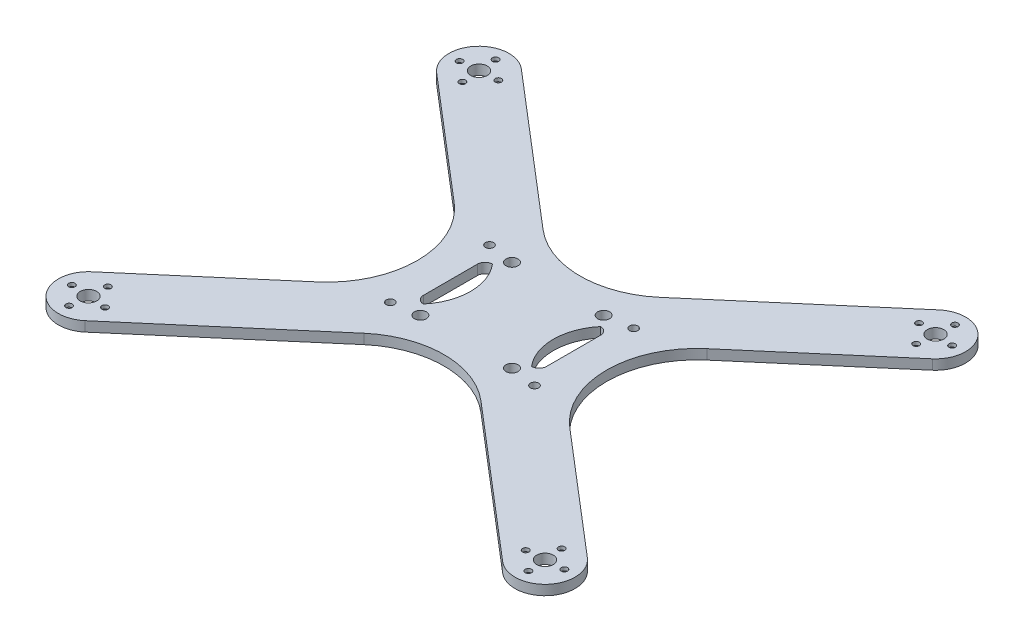
SolidWorks part; units mm, degrees
ref_plane "Front Plane" through (0, 0, 0) normal (0, 0, 1) x (1, 0, 0)
ref_plane "Top Plane" through (0, 0, 0) normal (0, 1, 0) x (1, 0, 0)
ref_plane "Right Plane" through (0, 0, 0) normal (1, 0, 0) x (0, 0, -1)
sketch "Sketch1" plane through (0, 0, 0) normal (0, 1, 0) x (1, 0, 0)
  line L0 (-75.9934, 65) -> (75.9934, -65) construction
  line L5 (-38.759, -33.152) -> (23.5603, 20.152) construction
  line L6 (-38.759, 33.152) -> (23.5603, -20.152) construction
  line L7 (75.9934, 65) -> (-75.9934, -65) construction
  line L8 (-82.4934, 57.4007) -> (-42.0385, 22.798)
  line L9 (82.4934, -57.4007) -> (42.0385, -22.798)
  line L10 (69.4934, 72.5993) -> (19.5, 29.8381)
  line L11 (-69.4934, -72.5993) -> (-19.5, -29.8381)
  line L12 (19.5, -29.8381) -> (69.4934, -72.5993)
  line L14 (42.0385, 22.798) -> (82.4934, 57.4007)
  line L15 (-42.0385, -22.798) -> (-82.4934, -57.4007)
  line L16 (-19.5, 29.8381) -> (-69.4934, 72.5993)
  arc A0 (-69.4934, 72.5993) -> (-82.4934, 57.4007) centre (-75.9934, 65) ccw
  arc A1 (82.4934, 57.4007) -> (69.4934, 72.5993) centre (75.9934, 65) ccw
  arc A2 (-82.4934, -57.4007) -> (-69.4934, -72.5993) centre (-75.9934, -65) ccw
  arc A3 (69.4934, -72.5993) -> (82.4934, -57.4007) centre (75.9934, -65) ccw
  arc A4 (-19.5, 29.8381) -> (19.5, 29.8381) centre (0, 52.6361) ccw
  arc A5 (-42.0385, 22.798) -> (-42.0385, -22.798) centre (-61.5385, 0) cw
  arc A6 (42.0385, 22.798) -> (42.0385, -22.798) centre (61.5385, 0) ccw
  arc A7 (-19.5, -29.8381) -> (19.5, -29.8381) centre (0, -52.6361) cw
  point P0 (0, 0)
  point P8 (0, 0)
  point P9 (0, 0)
  dimension "D3" = 20
  dimension "D5" = 30
  dimension "D8" = 30
  dimension "D1" = 130
  dimension "D4" = 100
extrude "Boss-Extrude1" add sketch "Sketch1" along normal blind 3.3
sketch "Sketch2" plane through (0, 3.3, 0) normal (0, 1, 0) x (1, 0, 0)
  line L0 (-75.527, 59.0182) -> (-76.4598, 70.9818) construction
  line L1 (-68.3941, 58.5) -> (-83.5928, 71.5) construction
  line L2 (-81.9753, 64.5336) -> (-70.0116, 65.4664) construction
  line L3 (0, 55.65) -> (0, -42.5584) construction
  line L4 (-46.159, 0) -> (52.0494, 0) construction
  line L5 (-19.5, 29.8381) -> (-69.4934, 72.5993) construction
  line L6 (-82.4934, 57.4007) -> (-42.0385, 22.798) construction
  line L8 (-24, -16.5) -> (24, -16.5) construction
  line L9 (-24, -16.5) -> (-24, 16.5) construction
  line L10 (-24, 16.5) -> (24, 16.5) construction
  line L11 (24, -16.5) -> (24, 16.5) construction
  line L12 (-24, -16.5) -> (24, 16.5) construction
  line L13 (-24, 16.5) -> (24, -16.5) construction
  circle A0 centre (-76.4598, 70.9818) radius 1.05
  arc A1 (-69.4934, 72.5993) -> (-82.4934, 57.4007) centre (-75.9934, 65) ccw construction
  circle A2 centre (-70.0116, 65.4664) radius 1.05
  circle A3 centre (-75.527, 59.0182) radius 1.05
  circle A4 centre (-81.9753, 64.5336) radius 1.05
  circle A5 centre (75.527, 59.0182) radius 1.05
  circle A6 centre (81.9753, 64.5336) radius 1.05
  circle A7 centre (76.4598, 70.9818) radius 1.05
  circle A8 centre (70.0116, 65.4664) radius 1.05
  circle A9 centre (-76.4598, -70.9818) radius 1.05
  circle A10 centre (-81.9753, -64.5336) radius 1.05
  circle A11 centre (-75.527, -59.0182) radius 1.05
  circle A12 centre (-70.0116, -65.4664) radius 1.05
  circle A13 centre (70.0116, -65.4664) radius 1.05
  circle A14 centre (76.4598, -70.9818) radius 1.05
  circle A15 centre (81.9753, -64.5336) radius 1.05
  circle A16 centre (75.527, -59.0182) radius 1.05
  circle A21 centre (-75.9934, 65) radius 2.75
  circle A22 centre (75.9934, 65) radius 2.75
  circle A23 centre (75.9934, -65) radius 2.75
  circle A24 centre (-75.9934, -65) radius 2.75
  circle A25 centre (-24, 16.5) radius 1.375
  circle A26 centre (24, 16.5) radius 1.375
  circle A27 centre (24, -16.5) radius 1.375
  circle A28 centre (-24, -16.5) radius 1.375
  point P0 (-75.9934, 65)
  point P12 (-75.9934, 65)
  point P18 (-75.9934, 65)
  point P19 (-75.9934, 65)
  point P51 (0, 0)
  dimension "D4" = 2.1
  dimension "D8" = 2.75
  dimension "D9" = 5.5
  dimension "D10" = 5.7574
  dimension "D11" = 5.7574
  dimension "D1" = 45
  dimension "D2" = 45
  dimension "D3" = 12
  dimension "D6" = 48
  dimension "D7" = 33
  dimension "D5" = 4
extrude "Cut-Extrude1" cut sketch "Sketch2" against normal up to surface (3.3 mm away) up to face at (0, 0, 0)
sketch "Sketch3" plane through (0, 0, 0) normal (0, -1, 0) x (1, 0, 0)
  line L0 (0, 46.2898) -> (0, -34.4776) construction
  line L1 (-50.4434, 0) -> (62.5036, 0) construction
  circle A0 centre (-76.4598, 70.9818) radius 1.9
  circle A2 centre (-70.0116, 65.4664) radius 1.9
  circle A3 centre (-75.527, 59.0182) radius 1.9
  circle A4 centre (-81.9753, 64.5336) radius 1.9
  circle A5 centre (-75.9934, 65) radius 2.75 construction
  circle A6 centre (81.9753, 64.5336) radius 1.9
  circle A7 centre (75.527, 59.0182) radius 1.9
  circle A8 centre (70.0116, 65.4664) radius 1.9
  circle A9 centre (76.4598, 70.9818) radius 1.9
  circle A10 centre (76.4598, -70.9818) radius 1.9
  circle A11 centre (70.0116, -65.4664) radius 1.9
  circle A12 centre (75.527, -59.0182) radius 1.9
  circle A13 centre (81.9753, -64.5336) radius 1.9
  circle A14 centre (-81.9753, -64.5336) radius 1.9
  circle A15 centre (-75.527, -59.0182) radius 1.9
  circle A16 centre (-70.0116, -65.4664) radius 1.9
  circle A17 centre (-76.4598, -70.9818) radius 1.9
  point P13 (-75.9934, 65)
  point P25 (75.9934, 65)
  point P34 (75.9934, -65)
  point P43 (-75.9934, -65)
  dimension "D1" = 3.8
  dimension "D2" = 4
extrude "Cut-Extrude2" cut sketch "Sketch3" against normal blind 2.15
sketch "Sketch4" plane through (0, 0, 0) normal (0, 1, 0) x (1, 0, 0)
  line L0 (-36.5, 25.325) -> (-36.5, -25.325) construction
  line L1 (-36.5, 25.325) -> (36.5, 25.325) construction
  line L2 (-15.25, 15.25) -> (15.25, 15.25) construction
  line L3 (-15.25, 15.25) -> (-15.25, -15.25) construction
  line L4 (15.25, 15.25) -> (15.25, -15.25) construction
  line L5 (15.25, -15.25) -> (-15.25, -15.25) construction
  circle A0 centre (36.5, 25.325) radius 1.375
  circle A1 centre (-36.5, 25.325) radius 1.375
  circle A2 centre (-36.5, -25.325) radius 1.375
  circle A3 centre (36.5, -25.325) radius 1.375
  circle A4 centre (-15.25, 15.25) radius 2
  circle A5 centre (15.25, 15.25) radius 2
  circle A6 centre (15.25, -15.25) radius 2
  circle A7 centre (-15.25, -15.25) radius 2
  point P8 (-36.5, 0)
  point P9 (0, 25.325)
  point P20 (0, 15.25)
  point P21 (-15.25, 0)
  dimension "D2" = 2.75
  dimension "D4" = 4
  dimension "D1" = 73
  dimension "D3" = 50.65
  dimension "D5" = 30.5
  dimension "D6" = 30.5
sketch "Sketch6" plane through (0, 3.3, 0) normal (0, 1, 0) x (1, 0, 0)
  line L0 (-18, 9) -> (-18, -9) construction
  line L1 (-18, 11.5) -> (-18, -11.5) construction
  line L3 (-20.5, 9) -> (-20.5, -9)
  line L4 (0, 12.4421) -> (0, -9.4721) construction
  line L5 (18, 11.5) -> (18, -11.5) construction
  line L8 (18, 9) -> (18, -9) construction
  line L9 (20.5, 9) -> (20.5, -9)
  circle A0 centre (-15.25, 15.25) radius 2
  circle A1 centre (15.25, 15.25) radius 2
  circle A2 centre (15.25, -15.25) radius 2
  circle A3 centre (-15.25, -15.25) radius 2
  arc A4 (-18, 11.5) -> (-20.5, 9) centre (-18, 9) ccw
  arc A5 (-20.5, -9) -> (-18, -11.5) centre (-18, -9) ccw
  arc A8 (-18, 11.5) -> (-18, -11.5) centre (-31.5385, 0) cw
  arc A9 (-42.0385, -22.798) -> (-42.0385, 22.798) centre (-61.5385, 0) ccw construction
  arc A10 (18, 11.5) -> (18, -11.5) centre (31.5385, 0) ccw
  arc A11 (20.5, -9) -> (18, -11.5) centre (18, -9) cw
  arc A12 (18, 11.5) -> (20.5, 9) centre (18, 9) cw
  point P16 (-18, 0)
  point P34 (-13.775, 0)
  point P35 (-20.5, 0)
  point P49 (18, 0)
  dimension "D1" = 4
  dimension "D4" = 2.5
  dimension "D6" = 17.7634
  dimension "D2" = 18
  dimension "D3" = 9
  dimension "D5" = 23
  dimension "D7" = 18
extrude "Cut-Extrude3" cut sketch "Sketch6" against normal blind 10
sketch "Sketch7" plane through (0, 0, 0) normal (0, 1, 0) x (1, 0, 0)
  line L0 (-15.25, 15.25) -> (-27, 0) construction
  line L5 (-16.8343, 16.4707) -> (-13.6657, 14.0293) construction
  line L6 (-16.8343, 16.4707) -> (-28.5843, 1.2207)
  line L7 (-46.159, 0) -> (52.0494, 0) construction
  line L8 (-28.5843, 1.2207) -> (-25.4157, -1.2207) construction
  line L9 (-13.6657, 14.0293) -> (-25.4157, -1.2207)
  line L10 (0, 0) -> (-7.6058, 0)
  circle A0 centre (-27, 0) radius 1
  arc A1 (-28.5843, 1.2207) -> (-25.4157, -1.2207) centre (-27, 0) ccw
  arc A2 (-13.6657, 14.0293) -> (-16.8343, 16.4707) centre (-15.25, 15.25) ccw
  circle A3 centre (-15.25, 15.25) radius 1
  point P2 (-15.25, 15.25)
  point P18 (-27, 0)
  dimension "D3" = 2
  dimension "D4" = 4
  dimension "D6" = 2
  dimension "D7" = 4
  dimension "D1" = 27
